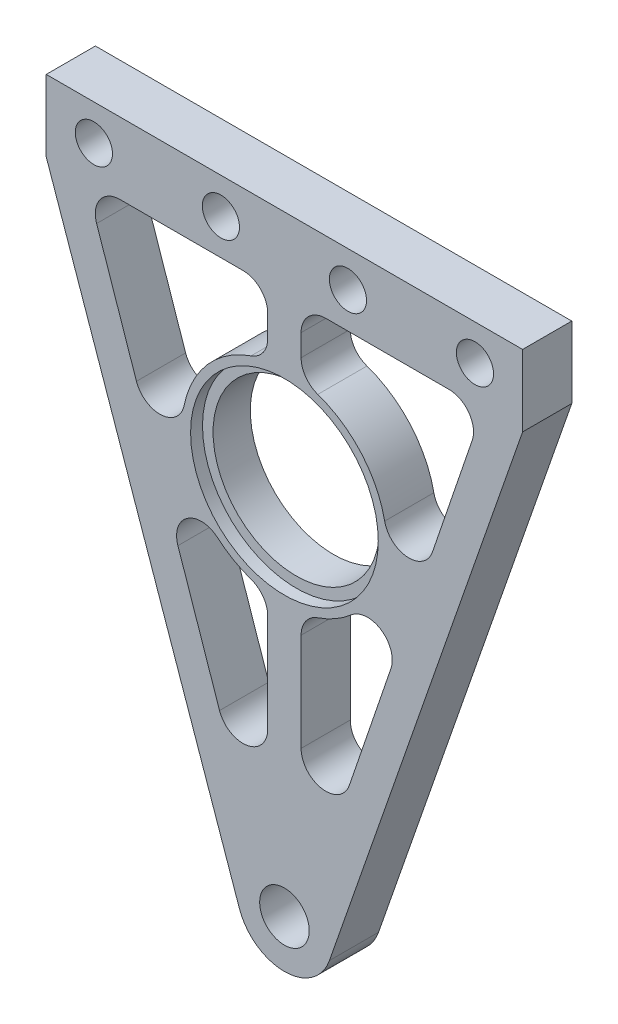
SolidWorks part; units mm, degrees
ref_plane "Front Plane" through (0, 0, 0) normal (0, 0, 1) x (1, 0, 0)
ref_plane "Top Plane" through (0, 0, 0) normal (0, 1, 0) x (1, 0, 0)
ref_plane "Right Plane" through (0, 0, 0) normal (1, 0, 0) x (0, 0, -1)
ref_plane "Plane1" through (0, 0, 6.5532) normal (0, 0, 1) x (1, 0, 0)
sketch "Sketch1" plane through (0, 0, 6.5532) normal (0, 0, 1) x (1, 0, 0)
  line L0 (24.3899, -74.0322) -> (50.1435, -0.1243)
  line L1 (50.1435, -0.1243) -> (50.1435, 9.4007)
  line L2 (50.1435, 9.4007) -> (-13.3565, 9.4007)
  line L3 (-13.3565, 9.4007) -> (-13.3565, -0.1243)
  line L4 (-13.3565, -0.1243) -> (12.3971, -74.0322)
  line L5 (18.3935, -71.9428) -> (18.3935, 9.4007) construction
  arc A0 (12.3971, -74.0322) -> (24.3899, -74.0322) centre (18.3935, -71.9428) ccw
  dimension "D1" = 6.35
  dimension "D2" = 71.8185
  dimension "D3" = 31.75
  dimension "D4" = 9.525
extrude "Boss-Extrude1" add sketch "Sketch1" against normal blind 6.5532
sketch "Sketch2" plane through (0, 0, 6.5532) normal (0, 0, 1) x (1, 0, 0)
  line L0 (20.616, -35.7941) -> (20.616, -51.4209)
  line L1 (27.0431, -52.487) -> (32.5901, -36.2264)
  arc A0 (20.616, -51.4209) -> (27.0431, -52.487) centre (23.918, -51.4209) ccw
  arc A1 (32.5901, -36.2264) -> (27.307, -32.6609) centre (29.4649, -35.1603) ccw
  arc A2 (27.307, -32.6609) -> (20.616, -35.7941) centre (18.3935, -22.3366) cw
extrude "Cut-Extrude1" cut sketch "Sketch2" against normal through all
sketch "Sketch3" plane through (0, 0, 6.5532) normal (0, 0, 1) x (1, 0, 0)
  line L0 (16.171, -51.4209) -> (16.171, -35.7941)
  line L1 (4.1969, -36.2264) -> (9.7438, -52.487)
  arc A0 (9.7438, -52.487) -> (16.171, -51.4209) centre (12.869, -51.4209) ccw
  arc A1 (16.171, -35.7941) -> (9.4799, -32.6609) centre (18.3935, -22.3366) cw
  arc A2 (9.4799, -32.6609) -> (4.1969, -36.2264) centre (7.3221, -35.1603) ccw
extrude "Cut-Extrude2" cut sketch "Sketch3" against normal through all
sketch "Sketch4" plane through (0, 0, 6.5532) normal (0, 0, 1) x (1, 0, 0)
  line L0 (38.119, -20.0185) -> (43.4274, -4.457)
  line L1 (40.3275, -0.1243) -> (20.616, -0.1243)
  line L2 (20.616, -0.1243) -> (20.616, -8.8791)
  arc A0 (20.616, -8.8791) -> (31.7584, -19.612) centre (18.3935, -22.3366) cw
  arc A1 (31.7584, -19.612) -> (38.119, -20.0185) centre (34.9938, -18.9524) ccw
  arc A2 (43.4274, -4.457) -> (40.3275, -0.1243) centre (40.3275, -3.3996) ccw
  point P9 (0, 0)
  point P10 (0, 0)
  point P11 (0, 0)
  point P12 (0, 0)
extrude "Cut-Extrude3" cut sketch "Sketch4" against normal through all
sketch "Sketch5" plane through (0, 0, 0) normal (0, 0, -1) x (-1, 0, 0)
  line L0 (1.3321, -20.0185) -> (6.6405, -4.457)
  line L1 (3.5406, -0.1243) -> (-16.171, -0.1243)
  line L2 (-16.171, -0.1243) -> (-16.171, -8.8791)
  arc A0 (-5.0286, -19.612) -> (1.3321, -20.0185) centre (-1.7931, -18.9524) ccw
  arc A1 (6.6405, -4.457) -> (3.5406, -0.1243) centre (3.5406, -3.3996) ccw
  arc A2 (-16.171, -8.8791) -> (-5.0286, -19.612) centre (-18.3935, -22.3366) cw
  point P9 (0, 0)
  point P10 (0, 0)
  point P11 (0, 0)
  point P12 (0, 0)
extrude "Cut-Extrude4" cut sketch "Sketch5" against normal through all
hole_wizard "1/4 Clearance Hole1" positions "Sketch7" profile "Sketch6" hole size "1/4" standard "ANSI Inch"
sketch "Sketch7" plane through (0, 0, 0) normal (0, 0, -1) x (-1, 0, 0)
  point P0 (-18.3935, -71.9426)
sketch "Sketch6" plane through (18.3935, -71.9426, 0) normal (1, 0, 0) x (0, 1, 0)
  line L0 (0, 0) -> (0, 6.5532)
  line L1 (0, 6.5532) -> (3.302, 6.5532)
  line L2 (3.302, 6.5532) -> (3.302, 0)
  line L5 (3.302, 0) -> (0, 0)
  line L11 (0, -6.35) -> (0, 107.95) construction
  dimension "Thru Hole Dia." = 6.604
  dimension "Thru Hole Depth" = 6.5532
hole_wizard "Hole1" positions "Sketch9" profile "Sketch8" legacy end condition through all
sketch "Sketch9" plane through (0, 0, 6.5532) normal (0, 0, 1) x (1, 0, 0)
  line L0 (-13.3565, 4.6382) -> (50.1435, 4.6382) construction
  line L1 (-13.3565, 9.4007) -> (-13.3565, -0.1243) construction
  line L2 (50.1435, -0.1243) -> (50.1435, 9.4007) construction
  circle A0 centre (18.3935, -71.9426) radius 3.302 construction
  point P0 (9.9277, 4.6382)
  point P1 (26.8593, 4.6382)
  point P2 (-7.0065, 4.6382)
  point P3 (43.7935, 4.6382)
  dimension "D1" = 8.4658
  dimension "D2" = 8.4658
  dimension "D3" = 16.9342
  dimension "D4" = 16.9342
sketch "Sketch8" plane through (9.9277, 4.6382, 6.5532) normal (1, 0, 0) x (0, -1, 0)
  line L0 (0, 0) -> (0, 6.5532)
  line L1 (0, 6.5532) -> (2.4765, 6.5532)
  line L2 (2.4765, 6.5532) -> (2.4765, 0)
  line L3 (2.4765, 0) -> (0, 0)
  line L4 (0, 110) -> (0, -10) construction
  dimension "Diameter" = 4.953
  dimension "Depth" = 6.5532
hole_wizard "Hole2" positions "Sketch11" profile "Sketch10" legacy
sketch "Sketch11" plane through (0, 0, 6.5532) normal (0, 0, 1) x (1, 0, 0)
  point P0 (18.3935, -22.3366)
sketch "Sketch10" plane through (18.3935, -22.3366, 6.5532) normal (1, 0, 0) x (0, -1, 0)
  line L0 (0, 0) -> (0, 6.5532)
  line L1 (0, 6.5532) -> (11.0998, 6.5532)
  line L2 (11.0998, 6.5532) -> (11.0998, 1.5875)
  line L3 (11.0998, 1.5875) -> (12.5095, 1.5875)
  line L4 (12.5095, 1.5875) -> (12.5095, 0)
  line L5 (12.5095, 0) -> (0, 0)
  line L6 (0, 110) -> (0, -10) construction
  dimension "Diameter" = 22.1996
  dimension "Depth" = 6.5532
  dimension "C-Bore Diameter" = 25.019
  dimension "C-Bore Depth" = 1.5875
fillet "Fillet1" radius 3.302 6 edges at (20.616, -0.1243, 3.2766) (20.616, -35.7941, 3.2766) (16.171, -35.7941, 3.2766) (16.171, -8.8791, 3.2766) (16.171, -0.1243, 3.2766) (20.616, -8.8791, 3.2766)
